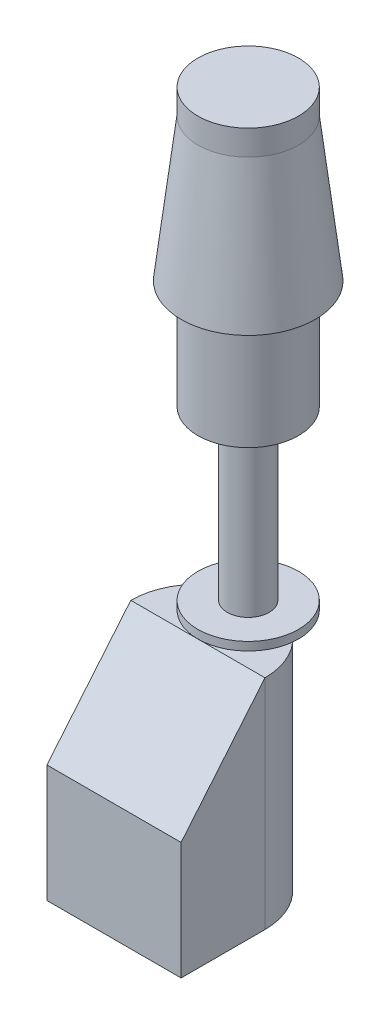
SolidWorks part; units mm, degrees
ref_plane "Front Plane" through (0, 0, 0) normal (0, 0, 1) x (1, 0, 0)
ref_plane "Top Plane" through (0, 0, 0) normal (0, 1, 0) x (1, 0, 0)
ref_plane "Right Plane" through (0, 0, 0) normal (1, 0, 0) x (0, 0, -1)
sketch "Sketch1" plane through (0, 0, 0) normal (0, 1, 0) x (1, 0, 0)
  circle A0 centre (0, 0) radius 38.1
  dimension "D1" = 76.2
extrude "Boss-Extrude1" add sketch "Sketch1" along normal mid plane 82.55
sketch "Sketch2" plane through (0, -41.275, 0) normal (0, -1, 0) x (1, 0, 0)
  circle A0 centre (0, 0) radius 15.875
  dimension "D1" = 31.75
extrude "Boss-Extrude2" add sketch "Sketch2" along normal blind 127
sketch "Sketch3" plane through (0, -168.275, 0) normal (0, -1, 0) x (1, 0, 0)
  circle A0 centre (0, 0) radius 38.1
  dimension "D1" = 76.2
extrude "Boss-Extrude3" add sketch "Sketch3" along normal blind 6.35
sketch "Sketch4" plane through (0, -174.625, 0) normal (0, -1, 0) x (1, 0, 0)
  line L0 (-50.8, 38.1) -> (50.8, 38.1) construction
  line L1 (0, -41.91) -> (0, 41.91) construction
  line L2 (-50.8, 38.1) -> (-50.8, 101.6)
  line L3 (-50.8, 101.6) -> (50.8, 101.6)
  line L4 (50.8, 101.6) -> (50.8, 38.1)
  circle A0 centre (0, 0) radius 12.7 construction
  circle A1 centre (0, 0) radius 38.1 construction
  arc A2 (-50.8, 38.1) -> (50.8, 38.1) centre (0, 38.1) ccw
  dimension "D1" = 101.6
  dimension "D2" = 50.8
  dimension "D3" = 63.5
extrude "Boss-Extrude4" add sketch "Sketch4" along normal blind 165.1
sketch "Sketch5" plane through (50.8, 0, 0) normal (1, 0, 0) x (0, 0, -1)
  line L0 (-38.1, -174.625) -> (-101.6, -174.625)
  line L1 (-101.6, -174.625) -> (-101.6, -250.825)
  line L2 (-101.6, -339.725) -> (-101.6, -174.625) construction
  line L3 (-101.6, -250.825) -> (-38.1, -174.625)
  dimension "D1" = 76.2
extrude "Cut-Extrude1" cut sketch "Sketch5" against normal up to surface (101.6 mm away) up to face at (-50.8, -257.175, 69.85)
sketch "Sketch6" plane through (0, 0, 0) normal (0, 0, 1) x (1, 0, 0)
  line L0 (0, 41.275) -> (50.8, 41.275)
  line L1 (38.1, 41.275) -> (-38.1, 41.275) construction
  line L2 (50.8, 41.275) -> (38.1, 149.225)
  line L3 (38.1, 149.225) -> (38.1, 168.275)
  line L4 (38.1, 168.275) -> (0, 168.275)
  line L5 (0, -76.835) -> (0, 76.835) construction
  line L6 (0, 168.275) -> (0, 41.275)
  dimension "D1" = 50.8
  dimension "D2" = 38.1
  dimension "D3" = 19.05
  dimension "D4" = 127
revolve "Revolve1" add sketch "Sketch6" angle 360 about L6
equation "\"D2@Sketch4\"=\"D1@Sketch4\"/2"
